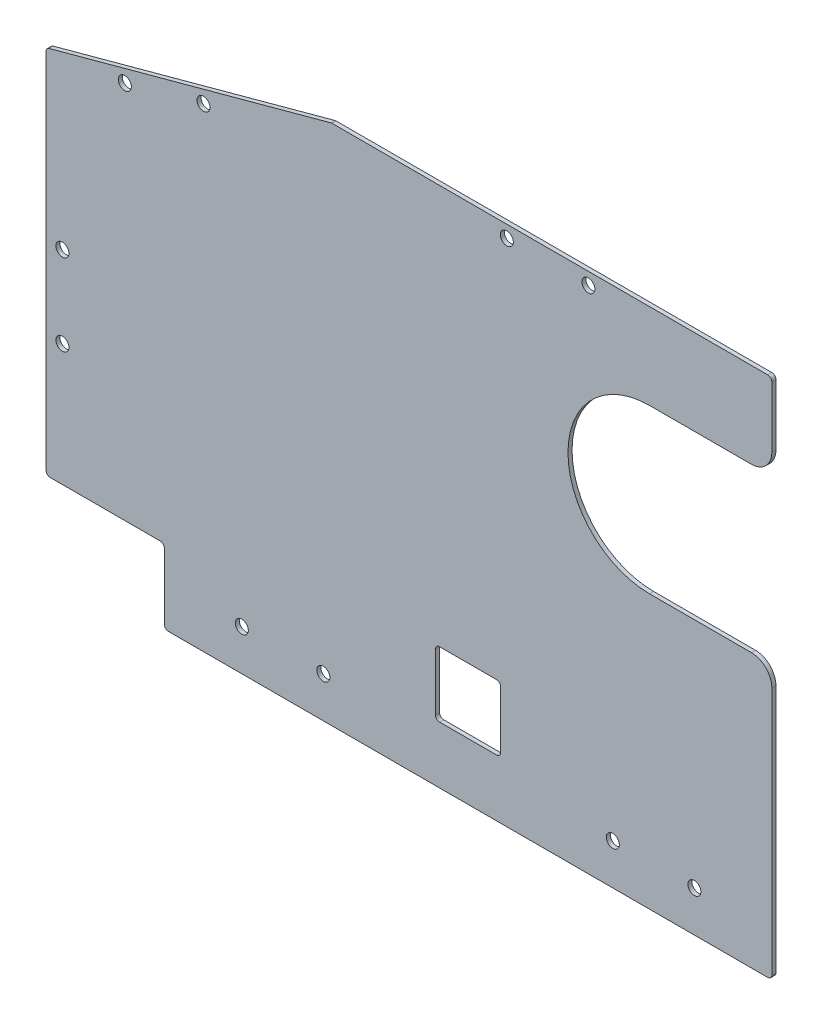
SolidWorks part; units mm, degrees
material "Thornel Mat VMA"
ref_plane "前视基准面" through (0, 0, 0) normal (0, 0, 1) x (1, 0, 0)
ref_plane "上视基准面" through (0, 0, 0) normal (0, 1, 0) x (1, 0, 0)
ref_plane "右视基准面" through (0, 0, 0) normal (1, 0, 0) x (0, 0, -1)
other "Configuration Table"
sketch "草图1" plane through (0, 0, 0) normal (0, 0, 1) x (1, 0, 0)
  line L0 (-10, 0) -> (10, 0) construction
  line L1 (0, 0) -> (0, -50000) construction
  line L3 (-45, -10) -> (45, -10)
  line L4 (-45, -10) -> (-45, 4)
  line L5 (-45, 4) -> (45, 4)
  line L6 (45, -10) -> (45, 4)
  line L7 (-45, -10) -> (45, 4) construction
  line L8 (-45, 4) -> (45, -10) construction
  point P4 (0, 0)
  point P8 (0, -3)
  dimension "D1" = 10
  dimension "D2" = 20
  dimension "D4" = 4
  dimension "D5" = 90
extrude "凸台-拉伸1" add sketch "草图1" along normal blind 1
sketch "草图2" plane through (0, 0, 1) normal (0, 0, 1) x (1, 0, 0)
  line L0 (45, 4) -> (-45, 4) construction
  line L2 (-85, 8.2) -> (-85, 4)
  line L3 (-85, 4) -> (64, 4)
  line L4 (64, 118) -> (64, 4)
  line L5 (-114, 98) -> (64, 118)
  line L6 (-85, 8.2) -> (-114, 8.2)
  line L9 (-114, 8.2) -> (-114, 98)
  line L10 (45, -10) -> (45, 4) construction
  line L11 (-45, 4) -> (-45, -10) construction
  dimension "D1" = 19
  dimension "D2" = 40
  dimension "D3" = 29
  dimension "D4" = 4.2
  dimension "D5" = 114
  dimension "D6" = 94
extrude "凸台-拉伸2" add sketch "草图2" against normal blind 1
sketch "草图4" plane through (0, 0, 1) normal (0, 0, 1) x (1, 0, 0)
  line L1 (-85, 4) -> (-45, 4)
  line L2 (-85, 4) -> (-85, -10)
  line L3 (-85, -10) -> (-45, -10)
  line L4 (-45, 4) -> (-45, -10)
  line L5 (64, 4) -> (45, 4)
  line L6 (64, 4) -> (64, -10)
  line L7 (64, -10) -> (45, -10)
  line L8 (45, 4) -> (45, -10)
extrude "凸台-拉伸3" add sketch "草图4" against normal up to surface (1 mm away) up to face at (-27, 22.84, 0)
sketch "草图7" plane through (0, 0, 1) normal (0, 0, 1) x (1, 0, 0)
  line L0 (-85, 0) -> (64, 0) construction
  line L1 (-85, 8.2) -> (-85, -10) construction
  line L2 (64, 118) -> (64, -10) construction
  line L3 (-85, -10) -> (64, -10) construction
  circle A0 centre (45, 0) radius 1.6
  circle A1 centre (25, 0) radius 1.6
  circle A2 centre (-66, 0) radius 1.6
  circle A3 centre (-46, 0) radius 1.6
  dimension "D2" = 3.2
  dimension "D3" = 20
  dimension "D4" = 19
  dimension "D5" = 20
  dimension "D1" = 10
  dimension "D6" = 19
extrude "切除-拉伸1" cut sketch "草图7" against normal blind 10
sketch "草图9" plane through (0, 0, 0) normal (0, 0, -1) x (-1, 0, 0)
  line L0 (110, 8.2) -> (110, 98.4494) construction
  line L1 (85, 8.2) -> (114, 8.2) construction
  line L2 (114, 98) -> (-64, 118) construction
  line L3 (114, 8.2) -> (114, 98) construction
  line L4 (115, 53.1) -> (50115, 53.1) construction
  circle A0 centre (110, 58.1) radius 1.6
  circle A1 centre (110, 38.1) radius 1.6
  point P14 (114, 53.1)
  dimension "D2" = 3.2
  dimension "D3" = 20
  dimension "D4" = 5
  dimension "D1" = 4
extrude "切除-拉伸3" cut sketch "草图9" against normal blind 10
sketch "草图10" plane through (0, 0, 1) normal (0, 0, 1) x (1, 0, 0)
  line L0 (-114, 98) -> (-114, 118)
  line L1 (-114, 118) -> (64, 118)
  line L2 (64, 118) -> (-114, 98)
extrude "凸台-拉伸4" add sketch "草图10" against normal up to surface (1 mm away) up to face at (-111.6, 58.1, 0)
sketch "草图11" plane through (0, 0, 1) normal (0, 0, 1) x (1, 0, 0)
  line L6 (-44, 118) -> (-114, 118)
  line L7 (64, 118) -> (-114, 118) construction
  line L8 (-114, 118) -> (-114, 99)
  line L9 (-114, 8.2) -> (-114, 118) construction
  line L10 (-114, 99) -> (-44, 118)
  line L11 (-85, 8.2) -> (-114, 8.2) construction
  dimension "D1" = 90.8
  dimension "D2" = 70
extrude "切除-拉伸4" cut sketch "草图11" against normal blind 10
sketch "草图13" plane through (0, 0, 1) normal (0, 0, 1) x (1, 0, 0)
  line L2 (-114, 8.2) -> (-114, 99) construction
  line L4 (-43.6001, 115) -> (-113.2141, 96.1048)
  line L5 (64, 115) -> (-43.6001, 115)
  line L6 (-43.6001, 115) -> (-114, 95.8915) construction
  line L7 (64, 115) -> (-43.6001, 115) construction
  circle A0 centre (-1, 115) radius 1.6
  circle A1 centre (19, 115) radius 1.6
  circle A2 centre (-75.3967, 106.3695) radius 1.6
  circle A3 centre (-94.6984, 101.1305) radius 1.6
  dimension "D2" = 3.2
  dimension "D3" = 20
  dimension "D4" = 20
  dimension "D5" = 45
  dimension "D6" = 20
  dimension "D1" = 3
extrude "切除-拉伸5" cut sketch "草图13" against normal blind 10
sketch "草图14" plane through (0, 0, 0) normal (0, 0, -1) x (-1, 0, 0)
  line L0 (-94, 77) -> (-34, 77) construction
  line L1 (-64, 118) -> (-64, -10) construction
  line L2 (-94, 97) -> (-34, 97)
  line L3 (-94, 57) -> (-34, 57)
  arc A0 (-94, 97) -> (-94, 57) centre (-94, 77) ccw
  arc A1 (-34, 57) -> (-34, 97) centre (-34, 77) ccw
  point P4 (-64, 77)
  dimension "D1" = 20
  dimension "D2" = 60
  dimension "D3" = 77
extrude "切除-拉伸6" cut sketch "草图14" against normal blind 10
fillet "圆角1" radius 5 2 edges at (64, 57, 0.5) (64, 97, 0.5)
fillet "圆角2" radius 1 7 edges at (64, 118, 0.5) (-44, 118, 0.5) (-114, 99, 0.5) (-114, 8.2, 0.5) (-85, 8.2, 0.5) (-85, -10, 0.5) (64, -10, 0.5)
sketch "草图15" plane through (0, 0, 1) normal (0, 0, 1) x (1, 0, 0)
  line L0 (-46, 0) -> (25, 0) construction
  line L1 (-10.5, 0) -> (-10.5, 12) construction
  line L2 (-18.5, 4) -> (-2.5, 4)
  line L3 (-18.5, 4) -> (-18.5, 20)
  line L4 (-18.5, 20) -> (-2.5, 20)
  line L5 (-2.5, 4) -> (-2.5, 20)
  line L6 (-18.5, 4) -> (-2.5, 20) construction
  line L7 (-18.5, 20) -> (-2.5, 4) construction
  line L8 (-84, -10) -> (63, -10) construction
  circle A0 centre (-10.5, 12) radius 8 construction
  point P4 (-10.5, 12)
  dimension "D2" = 16
  dimension "D1" = 14
extrude "切除-拉伸7" cut sketch "草图15" against normal blind 10
fillet "圆角3" radius 1 4 edges at (-2.5, 4, 0.5) (-18.5, 4, 0.5) (-2.5, 20, 0.5) (-18.5, 20, 0.5)
